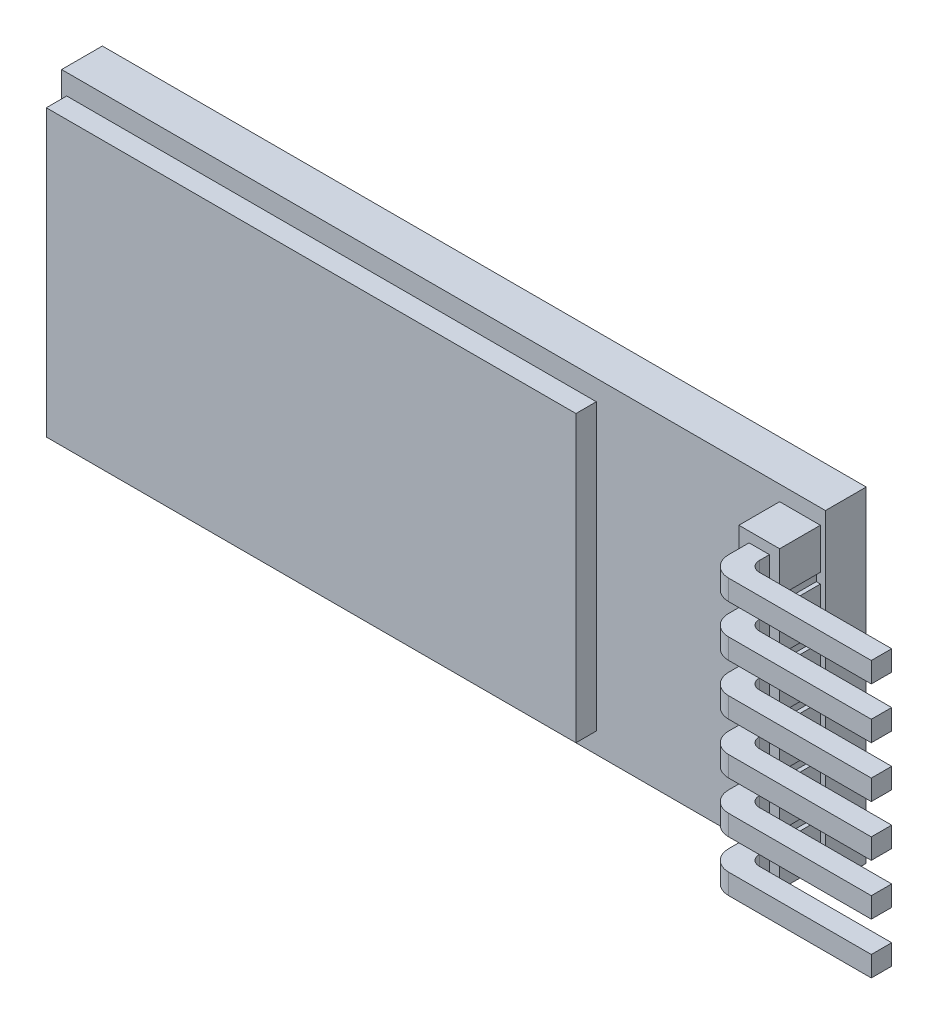
SolidWorks part; units mm, degrees
ref_plane "Front Plane" through (0, 0, 0) normal (0, 0, 1) x (1, 0, 0)
ref_plane "Top Plane" through (0, 0, 0) normal (0, 1, 0) x (1, 0, 0)
ref_plane "Right Plane" through (0, 0, 0) normal (1, 0, 0) x (0, 0, -1)
sketch "Sketch1" plane through (0, 0, 0) normal (0, 0, 1) x (1, 0, 0)
  line L1 (18.75, -8) -> (-18.75, -8)
  line L2 (18.75, -8) -> (18.75, 8)
  line L3 (18.75, 8) -> (-18.75, 8)
  line L4 (-18.75, -8) -> (-18.75, 8)
  line L5 (18.75, -8) -> (-18.75, 8) construction
  line L6 (18.75, 8) -> (-18.75, -8) construction
  point P0 (0, 0)
  dimension "D1" = 37.5
  dimension "D2" = 16
extrude "Boss-Extrude1" add sketch "Sketch1" along normal blind 2
sketch "Sketch2" plane through (0, 0, 2) normal (0, 0, 1) x (1, 0, 0)
  line L1 (-18.5, 7) -> (7.5, 7)
  line L2 (-18.5, 7) -> (-18.5, -7)
  line L3 (-18.5, -7) -> (7.5, -7)
  line L4 (7.5, 7) -> (7.5, -7)
  line L5 (18.75, 8) -> (-18.75, 8) construction
  line L6 (-18.75, -8) -> (18.75, -8) construction
  line L7 (-18.75, 8) -> (-18.75, -8) construction
  point P10 (0, 0)
  point P11 (0, 0)
  dimension "D1" = 26
  dimension "D2" = 1
  dimension "D3" = 1
  dimension "D4" = 0.25
extrude "Boss-Extrude2" add sketch "Sketch2" along normal blind 1
sketch "Sketch3" plane through (0, 0, 2) normal (0, 0, 1) x (1, 0, 0)
  line L0 (18.3, -5.25) -> (18.5, -5.25)
  line L1 (16.5, -7.25) -> (18.5, -7.25)
  line L2 (16.5, -7.25) -> (16.5, -5.25)
  line L3 (16.5, -5.25) -> (16.7, -5.25)
  line L4 (18.5, -7.25) -> (18.5, -5.25)
  line L6 (16.7, -5.25) -> (16.7, -4.75)
  line L8 (18.3, -5.25) -> (18.3, -4.75)
  line L9 (18.75, -8) -> (18.75, 8) construction
  line L10 (18.3, -2.75) -> (18.5, -2.75)
  line L11 (16.5, -4.75) -> (16.7, -4.75)
  line L12 (16.5, -4.75) -> (16.5, -2.75)
  line L13 (16.5, -2.75) -> (16.7, -2.75)
  line L14 (18.5, -4.75) -> (18.5, -2.75)
  line L15 (16.7, -2.75) -> (16.7, -2.25)
  line L16 (18.3, -2.75) -> (18.3, -2.25)
  line L17 (18.3, -0.25) -> (18.5, -0.25)
  line L18 (16.5, -2.25) -> (16.7, -2.25)
  line L19 (16.5, -2.25) -> (16.5, -0.25)
  line L20 (16.5, -0.25) -> (16.7, -0.25)
  line L21 (18.5, -2.25) -> (18.5, -0.25)
  line L22 (16.7, -0.25) -> (16.7, 0.25)
  line L23 (18.3, -0.25) -> (18.3, 0.25)
  line L24 (18.3, 2.25) -> (18.5, 2.25)
  line L25 (16.5, 0.25) -> (16.7, 0.25)
  line L26 (16.5, 0.25) -> (16.5, 2.25)
  line L27 (16.5, 2.25) -> (16.7, 2.25)
  line L28 (18.5, 0.25) -> (18.5, 2.25)
  line L29 (16.7, 2.25) -> (16.7, 2.75)
  line L30 (18.3, 2.25) -> (18.3, 2.75)
  line L31 (18.3, 4.75) -> (18.5, 4.75)
  line L32 (16.5, 2.75) -> (16.7, 2.75)
  line L33 (16.5, 2.75) -> (16.5, 4.75)
  line L34 (16.5, 4.75) -> (16.7, 4.75)
  line L35 (18.5, 2.75) -> (18.5, 4.75)
  line L36 (16.7, 4.75) -> (16.7, 5.25)
  line L37 (18.3, 4.75) -> (18.3, 5.25)
  line L38 (16.5, 7.25) -> (18.5, 7.25)
  line L39 (16.5, 5.25) -> (16.7, 5.25)
  line L40 (16.5, 5.25) -> (16.5, 7.25)
  line L41 (-18.75, -8) -> (18.75, -8) construction
  line L42 (18.5, 5.25) -> (18.5, 7.25)
  line L45 (18.3, 2.75) -> (18.5, 2.75)
  line L46 (18.3, 0.25) -> (18.5, 0.25)
  line L47 (18.3, -2.25) -> (18.5, -2.25)
  line L48 (18.3, -4.75) -> (18.5, -4.75)
  line L49 (18.3, 5.25) -> (18.5, 5.25)
  line L50 (18.3, 7.25) -> (18.3, 7.75) [skipped]
  line L51 (18.3, 7.25) -> (18.5, 7.25) [skipped]
  line L52 (16.7, 7.25) -> (16.7, 7.75) [skipped]
  line L53 (16.5, 7.25) -> (16.7, 7.25) [skipped]
  dimension "D1" = 2
  dimension "D2" = 0.2
  dimension "D3" = 0.2
  dimension "D4" = 0.5
  dimension "D5" = 0.25
  dimension "D7" = 0.75
  dimension "D6" = 6
extrude "Boss-Extrude3" add sketch "Sketch3" along normal blind 2
sketch "Sketch4" plane through (0, 0, 0) normal (0, 1, 0) x (1, 0, 0)
  line L0 (17, -4) -> (17, -5)
  line L1 (16.5, -4) -> (18.5, -4) construction
  line L2 (18, -6) -> (25, -6)
  line L3 (25, -6) -> (25, -5)
  line L4 (25, -5) -> (18.5, -5)
  line L5 (18, -4.5) -> (18, -4)
  line L6 (18, -4) -> (17, -4)
  line L7 (16.5, -4) -> (16.5, -2) construction
  arc A0 (17, -5) -> (18, -6) centre (18, -5) ccw
  arc A1 (18, -4.5) -> (18.5, -5) centre (18.5, -4.5) ccw
  point P12 (17, -6)
  point P13 (0, 0)
  point P14 (0, 0)
  dimension "D6" = 0.5
  dimension "D7" = 1
  dimension "D1" = 1
  dimension "D2" = 1
  dimension "D3" = 8
  dimension "D4" = 2
  dimension "D5" = 0.5
extrude "Boss-Extrude4" add sketch "Sketch4" against normal offset from surface 0.5 and the other way offset from surface (6.75 mm away) 0.5 up to face at (17.5, -7.25, 3) other way up to face at (17.5, 7.25, 3)
sketch "Sketch5" plane through (0, 0, 0) normal (1, 0, 0) x (0, 0, -1)
  line L0 (-6, -6.75) -> (-6, 6.75) construction
  line L1 (-6, -5.75) -> (-4, -5.75)
  line L2 (-6, -5.75) -> (-6, -4.25)
  line L3 (-6, -4.25) -> (-4, -4.25)
  line L4 (-4, -5.75) -> (-4, -4.25)
  line L5 (-4, -6.75) -> (-4, 6.75) construction
  line L6 (-5, -6.75) -> (-6, -6.75) construction
  line L7 (-6, -3.25) -> (-6, -1.75)
  line L8 (-6, -3.25) -> (-4, -3.25)
  line L9 (-4, -3.25) -> (-4, -1.75)
  line L10 (-6, -1.75) -> (-4, -1.75)
  line L11 (-6, -0.75) -> (-6, 0.75)
  line L12 (-6, -0.75) -> (-4, -0.75)
  line L13 (-4, -0.75) -> (-4, 0.75)
  line L14 (-6, 0.75) -> (-4, 0.75)
  line L15 (-6, 1.75) -> (-6, 3.25)
  line L16 (-6, 1.75) -> (-4, 1.75)
  line L17 (-4, 1.75) -> (-4, 3.25)
  line L18 (-6, 3.25) -> (-4, 3.25)
  line L19 (-6, 4.25) -> (-6, 5.75)
  line L20 (-6, 4.25) -> (-4, 4.25)
  line L21 (-4, 4.25) -> (-4, 5.75)
  line L22 (-6, 5.75) -> (-4, 5.75)
  dimension "D1" = 1
  dimension "D2" = 1.5
  dimension "D3" = 5
extrude "Cut-Extrude1" cut sketch "Sketch5" against normal through all both and the other way through all
